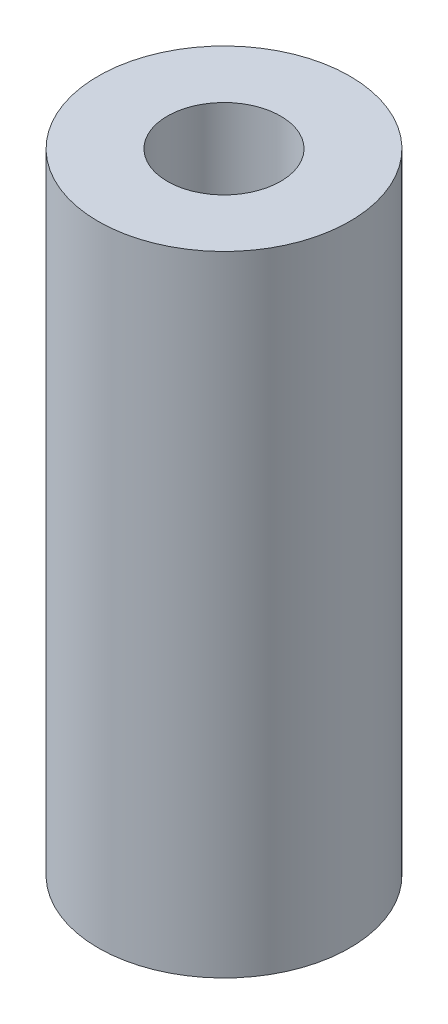
SolidWorks part; units mm, degrees
ref_plane "Front Plane" through (0, 0, 0) normal (0, 0, 1) x (1, 0, 0)
ref_plane "Top Plane" through (0, 0, 0) normal (0, 1, 0) x (1, 0, 0)
ref_plane "Right Plane" through (0, 0, 0) normal (1, 0, 0) x (0, 0, -1)
sketch "Sketch1" plane through (0, 0, 0) normal (0, 1, 0) x (1, 0, 0)
  circle A0 centre (0, 0) radius 1.8
  circle A1 centre (0, 0) radius 4
  dimension "D1" = 3.6
  dimension "D2" = 8
extrude "Boss-Extrude1" add sketch "Sketch1" along normal blind 20
